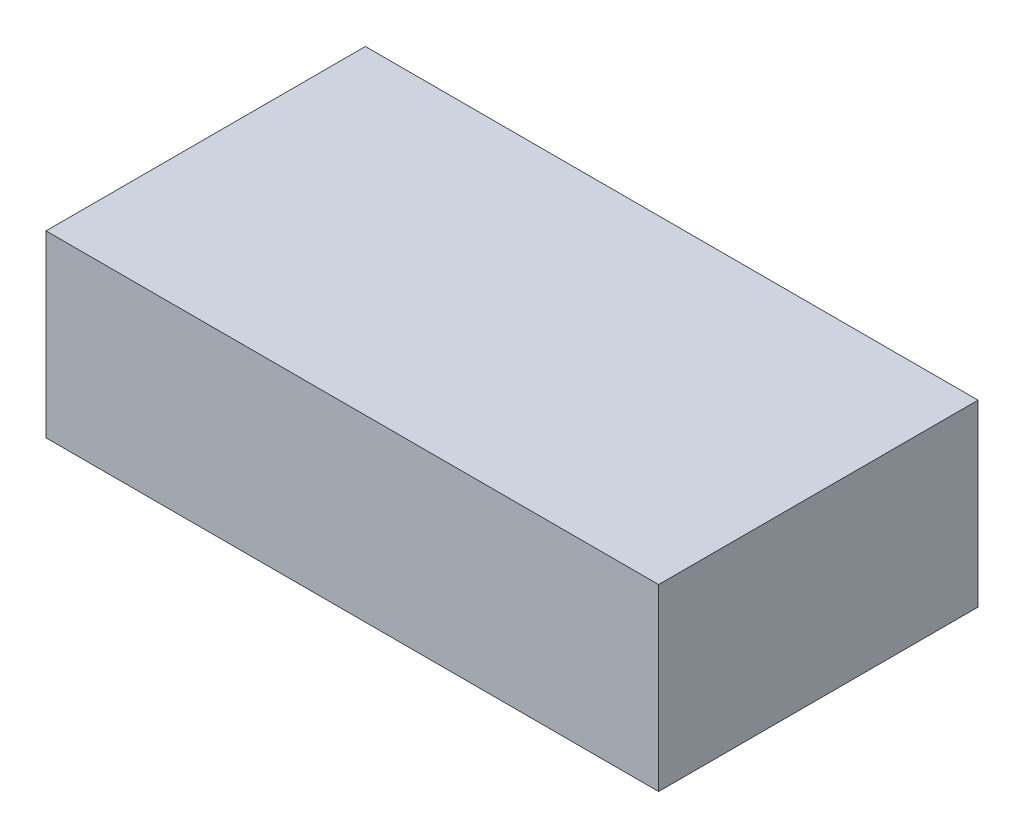
SolidWorks part; units mm, degrees
material "1060 合金"
ref_plane "前视基准面" through (0, 0, 0) normal (0, 0, 1) x (1, 0, 0)
ref_plane "上视基准面" through (0, 0, 0) normal (0, 1, 0) x (1, 0, 0)
ref_plane "右视基准面" through (0, 0, 0) normal (1, 0, 0) x (0, 0, -1)
sketch "草图3" plane through (0, 0, 0) normal (0, 0, 1) x (1, 0, 0)
  line L7 (111.25, -32.55) -> (-111.25, -32.55)
  line L8 (111.25, -32.55) -> (111.25, 32.55)
  line L9 (111.25, 32.55) -> (-111.25, 32.55)
  line L10 (-111.25, -32.55) -> (-111.25, 32.55)
  line L11 (111.25, -32.55) -> (-111.25, 32.55) construction
  line L12 (111.25, 32.55) -> (-111.25, -32.55) construction
  point P10 (0, 0)
  dimension "D1" = 222.5
  dimension "D2" = 65.1
extrude "凸台-拉伸1" add sketch "草图3" along normal blind 116 contours L9 L10 L7 L8
